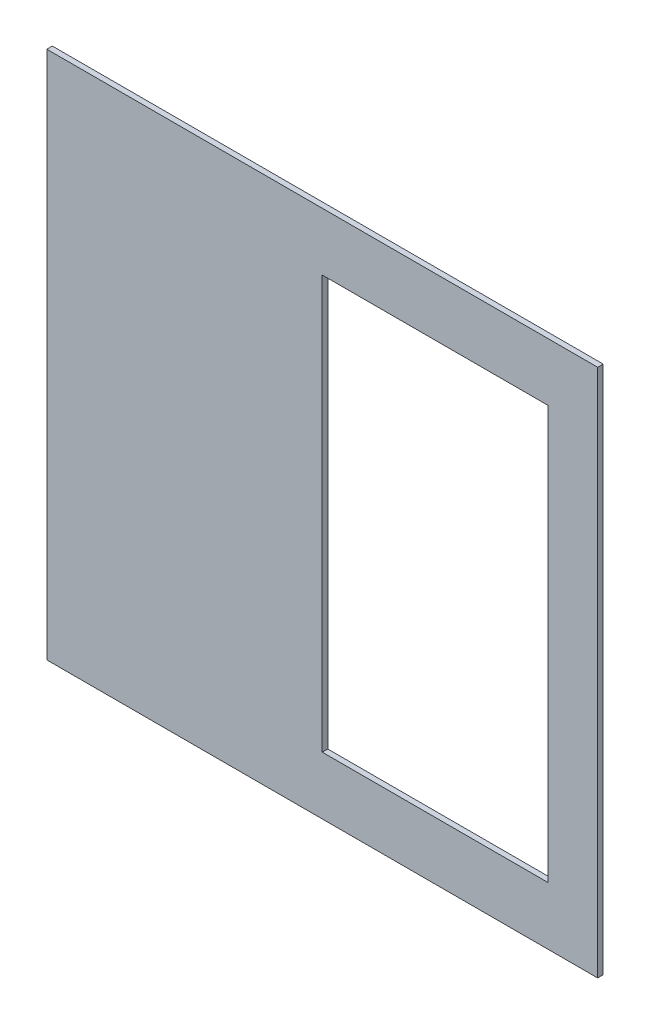
SolidWorks part; units mm, degrees
ref_plane "Front Plane" through (0, 0, 0) normal (0, 0, 1) x (1, 0, 0)
ref_plane "Top Plane" through (0, 0, 0) normal (0, 1, 0) x (1, 0, 0)
ref_plane "Right Plane" through (0, 0, 0) normal (1, 0, 0) x (0, 0, -1)
sketch "Sketch1" plane through (0, 0, 0) normal (0, 0, 1) x (1, 0, 0)
  line L1 (-317.5, -304.8) -> (317.5, -304.8)
  line L2 (-317.5, -304.8) -> (-317.5, 304.8)
  line L3 (-317.5, 304.8) -> (317.5, 304.8)
  line L4 (317.5, -304.8) -> (317.5, 304.8)
  line L5 (-317.5, -304.8) -> (317.5, 304.8) construction
  line L6 (-317.5, 304.8) -> (317.5, -304.8) construction
  point P0 (0, 0)
  dimension "D1" = 635
  dimension "D2" = 609.6
extrude "Boss-Extrude1" add sketch "Sketch1" along normal mid plane 6.35 contours L3 L4 L1 L2
sketch "Sketch2" plane through (0, 0, 3.175) normal (0, 0, 1) x (1, 0, 0)
  line L0 (55, 0) -> (-55, 0) construction
  line L1 (0, -238.125) -> (260.35, -238.125)
  line L2 (0, -238.125) -> (0, 238.125)
  line L3 (0, 238.125) -> (260.35, 238.125)
  line L4 (260.35, -238.125) -> (260.35, 238.125)
  line L5 (0, -238.125) -> (260.35, 238.125) construction
  line L6 (0, 238.125) -> (260.35, -238.125) construction
  line L7 (0, -55) -> (0, 55) construction
  point P0 (130.175, 0)
  dimension "D1" = 476.25
  dimension "D2" = 260.35
extrude "Cut-Extrude1" cut sketch "Sketch2" against normal through all
sketch "Sketch3" plane through (0, 0, 3.175) normal (0, 0, 1) x (1, 0, 0)
  line L0 (55, 0) -> (-55, 0) construction
  line L1 (-50.8, -238.125) -> (-15.875, -238.125)
  line L2 (-50.8, -238.125) -> (-50.8, 238.125)
  line L3 (-50.8, 238.125) -> (-15.875, 238.125)
  line L4 (-15.875, -238.125) -> (-15.875, 238.125)
  line L5 (-50.8, -238.125) -> (-15.875, 238.125) construction
  line L6 (-50.8, 238.125) -> (-15.875, -238.125) construction
  line L7 (260.35, 238.125) -> (0, 238.125) construction
  line L8 (0, -55) -> (0, 55) construction
  point P0 (-33.3375, 0)
  point P7 (-97.8455, 0)
  dimension "D1" = 34.925
  dimension "D2" = 15.875
extrude "Cut-Extrude2" [suppressed] cut sketch "Sketch3" against normal through all
pattern_linear "LPattern1" [suppressed] count 5 spacing 50.8
sketch "Sketch4" plane through (0, 0, 3.175) normal (0, 0, 1) x (1, 0, 0)
  line L0 (260.35, -238.125) -> (260.35, 238.125) construction
  line L1 (227.7991, 269.4433) -> (260.35, 269.4433) construction
  line L2 (227.7991, 269.4433) -> (227.7991, 248.0817) construction
  line L3 (227.7991, 248.0817) -> (260.35, 248.0817) construction
  line L4 (260.35, 269.4433) -> (260.35, 248.0817) construction
  line L5 (227.7991, 269.4433) -> (260.35, 248.0817) construction
  line L6 (227.7991, 248.0817) -> (260.35, 269.4433) construction
  line L7 (271.0308, 238.125) -> (290.9442, 238.125) construction
  line L8 (271.0308, 238.125) -> (271.0308, 206.5914) construction
  line L9 (271.0308, 206.5914) -> (290.9442, 206.5914) construction
  line L10 (290.9442, 238.125) -> (290.9442, 206.5914) construction
  line L11 (271.0308, 238.125) -> (290.9442, 206.5914) construction
  line L12 (271.0308, 206.5914) -> (290.9442, 238.125) construction
  line L13 (263.525, 276.225) -> (298.45, 276.225)
  line L14 (263.525, 276.225) -> (263.525, 241.3)
  line L15 (263.525, 241.3) -> (298.45, 241.3)
  line L16 (298.45, 276.225) -> (298.45, 241.3)
  line L17 (263.525, 276.225) -> (298.45, 241.3) construction
  line L18 (263.525, 241.3) -> (298.45, 276.225) construction
  line L19 (260.35, 238.125) -> (0, 238.125) construction
  point P0 (244.0746, 258.7625)
  point P5 (280.9875, 222.3582)
  point P10 (280.9875, 258.7625)
  point P15 (0, 0)
  point P16 (0, 0)
  point P21 (280.9875, 238.125)
  point P22 (0, 0)
  dimension "D1" = 34.925
  dimension "D2" = 34.925
  dimension "D3" = 3.175
  dimension "D4" = 3.175
extrude "Cut-Extrude3" [suppressed] cut sketch "Sketch4" against normal through all
pattern_linear "LPattern2" [suppressed] count 15 spacing 38.1 count 15 spacing 38.1
